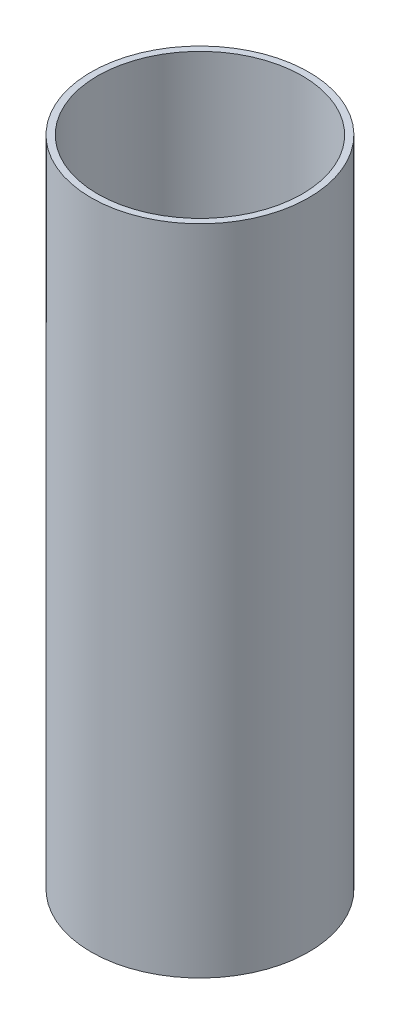
SolidWorks part; units mm, degrees
ref_plane "Front Plane" through (0, 0, 0) normal (0, 0, 1) x (1, 0, 0)
ref_plane "Top Plane" through (0, 0, 0) normal (0, 1, 0) x (1, 0, 0)
ref_plane "Right Plane" through (0, 0, 0) normal (1, 0, 0) x (0, 0, -1)
sketch "Sketch1" plane through (0, 0, 0) normal (0, 1, 0) x (1, 0, 0)
  circle A0 centre (0, 0) radius 50
  circle A1 centre (0, 0) radius 47
  dimension "D1" = 100
  dimension "D2" = 94
extrude "Boss-Extrude1" add sketch "Sketch1" along normal blind 300
